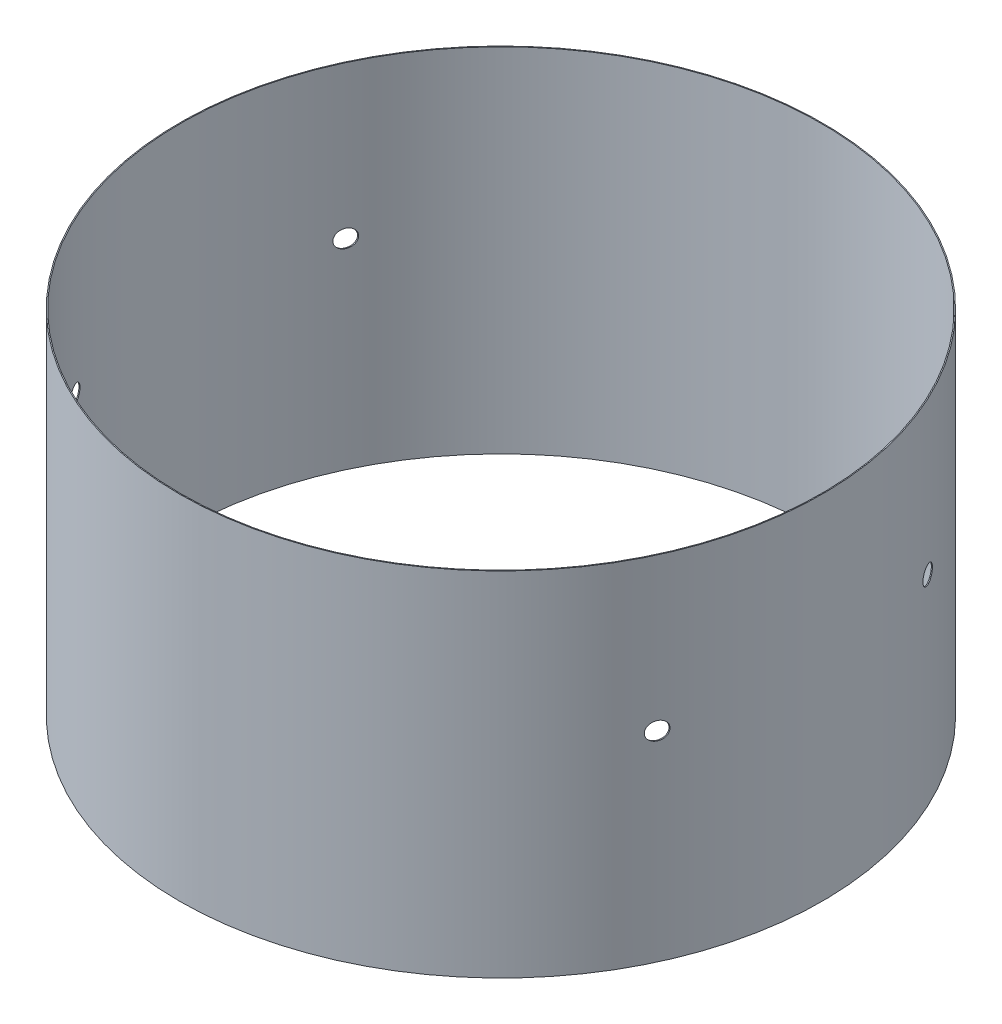
SolidWorks part; units mm, degrees
material "ASTM A36 Steel"
ref_plane "Front Plane" through (0, 0, 0) normal (0, 0, 1) x (1, 0, 0)
ref_plane "Top Plane" through (0, 0, 0) normal (0, 1, 0) x (1, 0, 0)
ref_plane "Right Plane" through (0, 0, 0) normal (1, 0, 0) x (0, 0, -1)
sketch "Sketch1" plane through (0, 0, 0) normal (0, 1, 0) x (1, 0, 0)
  circle A0 centre (0, 0) radius 500
  circle A1 centre (0, 0) radius 501.5
  dimension "D1" = 1000
  dimension "D2" = 1.5
extrude "Boss-Extrude1" add sketch "Sketch1" along normal blind 550
sketch "Sketch2" plane through (0, 0, 0) normal (1, 0, 0) x (0, 0, -1)
  line L0 (-501.5, 0) -> (501.5, 0) construction
  circle A0 centre (211, 312.5) radius 13.75
  circle A1 centre (-211, 312.5) radius 13.75
  dimension "D1" = 27.5
  dimension "D2" = 27.5
  dimension "D3" = 211
  dimension "D4" = 211
  dimension "D5" = 312.5
  dimension "D6" = 312.5
extrude "Cut-Extrude2" cut sketch "Sketch2" against normal through all both and the other way through all
